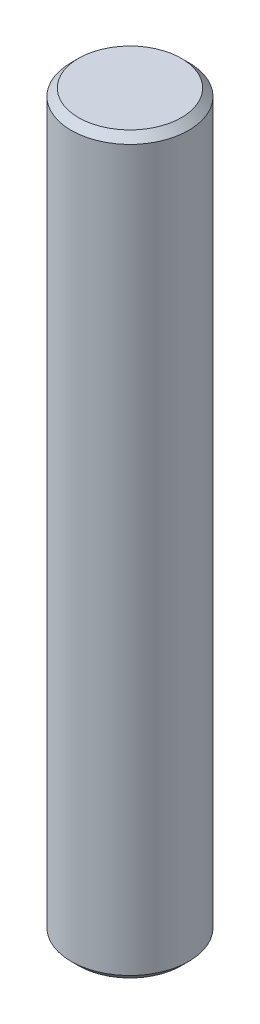
SolidWorks part; units mm, degrees
ref_plane "前视基准面" through (0, 0, 0) normal (0, 0, 1) x (1, 0, 0)
ref_plane "上视基准面" through (0, 0, 0) normal (0, 1, 0) x (1, 0, 0)
ref_plane "右视基准面" through (0, 0, 0) normal (1, 0, 0) x (0, 0, -1)
sketch "草图1" plane through (0, 0, 0) normal (0, 1, 0) x (1, 0, 0)
  circle A0 centre (0, 0) radius 8
  dimension "D1" = 16
extrude "凸台-拉伸1" add sketch "草图1" along normal blind 100
chamfer "倒角1" distance 1 angle 45 2 edges at (0, 0, 8) (0, 100, 8)
